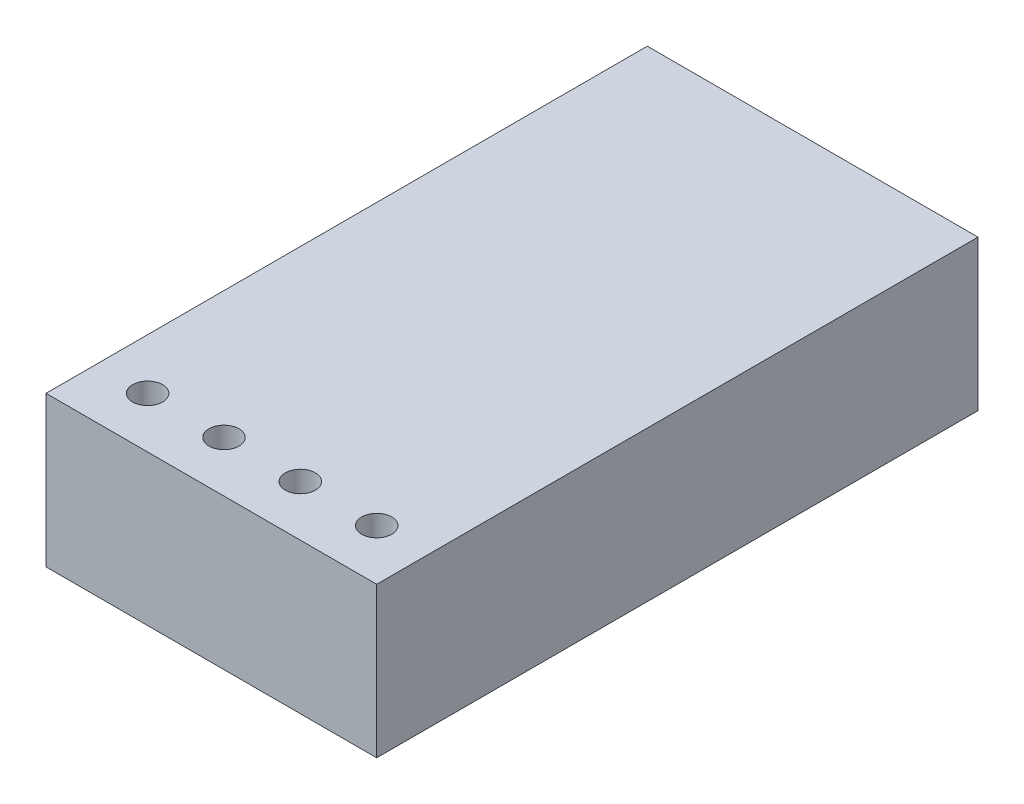
SolidWorks part; units mm, degrees
ref_plane "Front Plane" through (0, 0, 0) normal (0, 0, 1) x (1, 0, 0)
ref_plane "Top Plane" through (0, 0, 0) normal (0, 1, 0) x (1, 0, 0)
ref_plane "Right Plane" through (0, 0, 0) normal (1, 0, 0) x (0, 0, -1)
sketch "Sketch1" plane through (0, 0, 0) normal (0, 1, 0) x (1, 0, 0)
  line L0 (-5.5, -8.31) -> (-3.81, -8.31) construction
  line L1 (5.5, 10) -> (-5.5, 10)
  line L2 (5.5, 10) -> (5.5, -10)
  line L3 (5.5, -10) -> (-5.5, -10)
  line L4 (-5.5, 10) -> (-5.5, -10)
  line L5 (5.5, 10) -> (-5.5, -10) construction
  line L6 (5.5, -10) -> (-5.5, 10) construction
  line L7 (-3.81, -8.31) -> (-3.81, -10) construction
  line L8 (3.81, -8.31) -> (5.5, -8.31) construction
  circle A0 centre (-3.81, -8.31) radius 0.5
  circle A1 centre (-1.27, -8.31) radius 0.5
  circle A2 centre (1.27, -8.31) radius 0.5
  circle A3 centre (3.81, -8.31) radius 0.5
  point P0 (0, 0)
  point P15 (-1.1891, -8.0674)
  dimension "D3" = 1
  dimension "D1" = 11
  dimension "D2" = 20
  dimension "D5" = 2.54
  dimension "D4" = 4
extrude "Boss-Extrude1" add sketch "Sketch1" along normal blind 5
